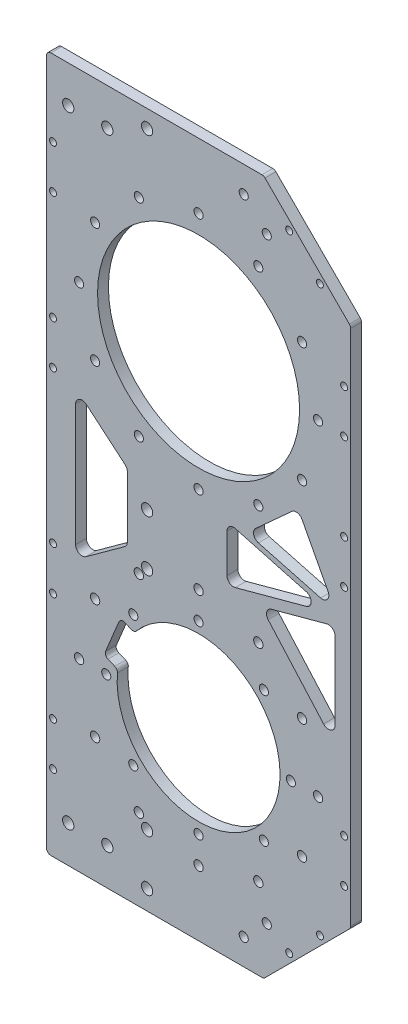
SolidWorks part; units mm, degrees
material "Thornel Mat VMA"
ref_plane "前视基准面" through (0, 0, 0) normal (0, 0, 1) x (1, 0, 0)
ref_plane "上视基准面" through (0, 0, 0) normal (0, 1, 0) x (1, 0, 0)
ref_plane "右视基准面" through (0, 0, 0) normal (1, 0, 0) x (0, 0, -1)
other "Configuration Table"
sketch "草图1" plane through (0, 0, 0) normal (0, 0, 1) x (1, 0, 0)
  line L1 (-70, -160) -> (70, -160)
  line L2 (-70, -160) -> (-70, 160)
  line L3 (-70, 160) -> (70, 160)
  line L4 (70, -160) -> (70, 160)
  line L5 (-70, -160) -> (70, 160) construction
  line L6 (-70, 160) -> (70, -160) construction
  point P0 (0, 0)
  dimension "D1" = 140
  dimension "D2" = 320
extrude "凸台-拉伸1" add sketch "草图1" along normal blind 5
sketch "草图2" plane through (0, 0, 5) normal (0, 0, 1) x (1, 0, 0)
  line L0 (-70, 0) -> (70, 0) construction
  line L1 (-70, 160) -> (-70, -160) construction
  line L2 (70, -160) -> (70, 160) construction
  line L3 (0, -75) -> (0, 75) construction
  circle A0 centre (0, 75) radius 46.5
  circle A1 centre (0, -75) radius 37.5
  circle A2 centre (0, -75) radius 42.5 construction
  circle A3 centre (42.5, -75) radius 2.1
  circle A4 centre (30.052, -105.052) radius 2.1
  circle A5 centre (0, -117.5) radius 2.1
  circle A6 centre (-30.052, -105.052) radius 2.1
  circle A7 centre (-42.5, -75) radius 2.1
  circle A8 centre (-30.052, -44.948) radius 2.1
  circle A9 centre (0, -32.5) radius 2.1
  circle A10 centre (30.052, -44.948) radius 2.1
  point P29 (0, -75)
  dimension "D1" = 75
  dimension "D2" = 93
  dimension "D3" = 150
  dimension "D4" = 70
  dimension "D5" = 85
  dimension "D6" = 4.2
  dimension "D8" = 75
  dimension "D7" = 8
extrude "切除-拉伸1" cut sketch "草图2" against normal blind 5
sketch "草图3" plane through (0, 0, 5) normal (0, 0, 1) x (1, 0, 0)
  line L0 (0, -75) -> (-30.052, -44.948) construction
  line L1 (0, -75) -> (-42.5, -75) construction
  line L2 (0, -75) -> (-43.6723, -56.9103) construction
  line L3 (-43.5537, -67.7834) -> (-17.685, -78.4985)
  line L4 (-43.5537, -67.7834) -> (-35.9, -49.3058)
  line L5 (-17.685, -78.4985) -> (-10.0314, -60.021)
  line L6 (-35.9, -49.3058) -> (-10.0314, -60.021)
  line L7 (-43.5537, -67.7834) -> (-10.0314, -60.021) construction
  line L8 (-17.685, -78.4985) -> (-35.9, -49.3058) construction
  point P8 (-26.7925, -63.9022)
  dimension "D1" = 22.5
  dimension "D2" = 20
  dimension "D3" = 15
  dimension "D4" = 28
extrude "切除-拉伸2" cut sketch "草图3" against normal blind 5
sketch "草图4" plane through (0, 0, 5) normal (0, 0, 1) x (1, 0, 0)
  circle A0 centre (0, -75) radius 55 construction
  circle A1 centre (0, -20) radius 2.15
  circle A2 centre (27.5, -27.3686) radius 2.15
  circle A3 centre (47.6314, -47.5) radius 2.15
  circle A4 centre (55, -75) radius 2.15
  circle A5 centre (47.6314, -102.5) radius 2.15
  circle A6 centre (27.5, -122.6314) radius 2.15
  circle A7 centre (0, -130) radius 2.15
  circle A8 centre (-27.5, -122.6314) radius 2.15
  circle A9 centre (-47.6314, -102.5) radius 2.15
  circle A10 centre (-55, -75) radius 2.15
  circle A11 centre (-47.6314, -47.5) radius 2.15
  circle A12 centre (-27.5, -27.3686) radius 2.15
  point P30 (0, -75)
  dimension "D1" = 110
  dimension "D2" = 4.3
  dimension "D3" = 12
extrude "切除-拉伸3" cut sketch "草图4" against normal blind 5
sketch "草图5" plane through (0, 0, 0) normal (0, 0, -1) x (-1, 0, 0)
  circle A0 centre (0, 75) radius 55 construction
  circle A1 centre (0, 130) radius 2.1
  circle A2 centre (27.5, 122.6314) radius 2.1
  circle A3 centre (47.6314, 102.5) radius 2.1
  circle A4 centre (55, 75) radius 2.1
  circle A5 centre (47.6314, 47.5) radius 2.1
  circle A6 centre (27.5, 27.3686) radius 2.1
  circle A7 centre (0, 20) radius 2.1
  circle A8 centre (-27.5, 27.3686) radius 2.1
  circle A9 centre (-47.6314, 47.5) radius 2.1
  circle A10 centre (-55, 75) radius 2.1
  circle A11 centre (-47.6314, 102.5) radius 2.1
  circle A12 centre (-27.5, 122.6314) radius 2.1
  point P29 (0, 75)
  dimension "D1" = 110
  dimension "D2" = 4.2
  dimension "D3" = 12
extrude "切除-拉伸4" cut sketch "草图5" against normal blind 15
sketch "草图6" plane through (0, 0, 5) normal (0, 0, 1) x (1, 0, 0)
  line L0 (30, 160) -> (70, 120)
  line L1 (70, 160) -> (-70, 160) construction
  line L2 (70, -160) -> (70, 160) construction
  line L3 (70, 120) -> (70, 160)
  line L4 (70, 160) -> (30, 160)
  line L5 (70, -120) -> (70, -160)
  line L6 (70, -160) -> (30, -160)
  line L7 (-70, -160) -> (70, -160) construction
  line L8 (30, -160) -> (70, -120)
  dimension "D1" = 45
  dimension "D2" = 45
  dimension "D3" = 40
  dimension "D4" = 40
extrude "切除-拉伸5" cut sketch "草图6" against normal blind 10
sketch "草图7" plane through (0, 0, 5) normal (0, 0, 1) x (1, 0, 0)
  line L0 (70, -115.7574) -> (25.7574, -160) construction
  line L1 (70, -120) -> (70, 120) construction
  line L2 (-70, -160) -> (30, -160) construction
  line L3 (70, -120) -> (30, -160) construction
  line L4 (-70, 0) -> (70, 0) construction
  line L5 (-70, 160) -> (-70, -160) construction
  line L6 (70, 115.7574) -> (25.7574, 160) construction
  circle A0 centre (41.7157, -144.0416) radius 1.6
  circle A1 centre (55.8579, -129.8995) radius 1.6
  circle A2 centre (55.8579, 129.8995) radius 1.6
  circle A3 centre (41.7157, 144.0416) radius 1.6
  dimension "D2" = 3.2
  dimension "D3" = 20
  dimension "D4" = 20
  dimension "D1" = 3
extrude "切除-拉伸6" cut sketch "草图7" against normal blind 327
fillet "圆角1" radius 2 9 edges at (70, -120, 2.5) (30, -160, 2.5) (-70, 160, 2.5) (30, 160, 2.5) (70, 120, 2.5) (-37.2178, -70.4078, 2.5) (-29.5641, -51.9302, 2.5) (-35.9, -49.3058, 2.5) (-70, -160, 2.5)
fillet "圆角2" radius 2 1 edges at (-43.5537, -67.7834, 2.5)
sketch "草图9" plane through (0, 0, 5) normal (0, 0, 1) x (1, 0, 0)
  line L0 (-23.7, 160) -> (-23.7, -160) construction
  line L1 (29.1716, 160) -> (-68, 160) construction
  line L2 (-68, -160) -> (29.1716, -160) construction
  line L3 (-70, 0.25) -> (70, 0.25) construction
  line L4 (-70, 158) -> (-70, -158) construction
  line L5 (70, -119.1716) -> (70, 119.1716) construction
  circle A0 centre (-23.7, 0) radius 2.6
  circle A1 centre (-23.7, -23.5) radius 2.6
  circle A2 centre (-23.7, -151) radius 2.6
  circle A3 centre (-23.7, -127.5) radius 2.6
  dimension "D2" = 5.2
  dimension "D3" = 23.5
  dimension "D5" = 23.5
  dimension "D6" = 9
  dimension "D1" = 159.75
  dimension "D4" = 46.3
extrude "切除-拉伸8" cut sketch "草图9" against normal blind 10
sketch "草图10" plane through (0, 0, 5) normal (0, 0, 1) x (1, 0, 0)
  line L0 (-68, -160) -> (29.1716, -160) construction
  line L1 (-70, 158) -> (-70, -158) construction
  line L2 (-70, 0) -> (70, 0) construction
  line L3 (70, -119.1716) -> (70, 119.1716) construction
  line L4 (-60, 143) -> (-42, 143) construction
  circle A0 centre (-60, -143) radius 2.6
  circle A1 centre (-60, 143) radius 2.6
  circle A2 centre (-42, 143) radius 2.6
  circle A3 centre (-42, -143) radius 2.6
  dimension "D1" = 17
  dimension "D2" = 5.2
  dimension "D3" = 10
  dimension "D4" = 5.2
  dimension "D5" = 18
extrude "切除-拉伸9" cut sketch "草图10" against normal blind 10
sketch "草图11" plane through (0, 0, 5) normal (0, 0, 1) x (1, 0, 0)
  line L0 (29.1716, 160) -> (-68, 160) construction
  line L1 (-70, 158) -> (-70, -158) construction
  circle A0 centre (-23.7, 152) radius 2.6
  dimension "D1" = 5.2
  dimension "D2" = 8
  dimension "D3" = 46.3
extrude "切除-拉伸10" cut sketch "草图11" against normal blind 10
sketch "草图12" plane through (0, 0, 5) normal (0, 0, 1) x (1, 0, 0)
  line L0 (67, 123) -> (67, -123) construction
  line L1 (30.5858, 159.4142) -> (69.4142, 120.5858) construction
  line L2 (69.4142, -120.5858) -> (30.5858, -159.4142) construction
  line L3 (70, -119.1716) -> (70, 119.1716) construction
  circle A0 centre (67, -104.5858) radius 1.6
  circle A1 centre (67, -84.5858) radius 1.6
  circle A2 centre (67, 94.5858) radius 1.6
  circle A3 centre (67, 74.5858) radius 1.6
  circle A4 centre (67, 34.5858) radius 1.6
  circle A5 centre (67, 14.5858) radius 1.6
  dimension "D2" = 3.2
  dimension "D3" = 20
  dimension "D4" = 20
  dimension "D5" = 20
  dimension "D6" = 26
  dimension "D7" = 40
  dimension "D8" = 16
  dimension "D1" = 3
extrude "切除-拉伸11" cut sketch "草图12" against normal blind 10
sketch "草图13" plane through (0, 0, 5) normal (0, 0, 1) x (1, 0, 0)
  line L0 (8.7868, 160) -> (70, 98.7868) construction
  line L1 (29.1716, 160) -> (-68, 160) construction
  line L2 (70, -119.1716) -> (70, 119.1716) construction
  line L3 (30.5858, 159.4142) -> (69.4142, 120.5858) construction
  line L4 (-70, 0) -> (70, 0) construction
  line L5 (-70, 158) -> (-70, -158) construction
  line L6 (8.7868, -160) -> (70, -98.7868) construction
  circle A0 centre (20.7868, 148) radius 2.1
  circle A1 centre (31.3934, 137.3934) radius 2.1
  circle A2 centre (31.3934, -137.3934) radius 2.1
  circle A3 centre (20.7868, -148) radius 2.1
  dimension "D2" = 4.2
  dimension "D3" = 15
  dimension "D4" = 12
  dimension "D1" = 15
extrude "切除-拉伸12" cut sketch "草图13" against normal blind 10
sketch "草图14" plane through (0, 0, 5) normal (0, 0, 1) x (1, 0, 0)
  line L0 (13.0829, 13.8401) -> (13.0829, -11.7624)
  line L1 (13.0829, -11.7624) -> (60.3054, 1.0388)
  line L2 (60.3054, 1.0388) -> (13.0829, 13.8401)
  line L3 (62.8087, -3.1145) -> (28.8071, -12.3318)
  line L4 (28.8071, -12.3318) -> (62.8087, -50.6783)
  line L5 (62.8087, -50.6783) -> (62.8087, -3.1145)
  line L6 (45.8053, 35.2514) -> (22.2063, 13.8401)
  line L7 (22.2063, 13.8401) -> (62.8087, 3.012)
  line L8 (62.8087, 3.012) -> (45.8053, 35.2514)
  line L9 (-56.6195, 32.2096) -> (-56.6195, -36.2538)
  line L10 (-56.6195, -36.2538) -> (-32.7974, -18.9626)
  line L11 (-32.7974, -18.9626) -> (-32.7974, 12.0751)
  line L12 (-32.7974, 12.0751) -> (-56.6195, 32.2096)
extrude "切除-拉伸13" cut sketch "草图14" against normal blind 10
fillet "圆角3" radius 3 6 edges at (60.3054, 1.0388, 2.5) (13.0829, 13.8401, 2.5) (62.8087, -50.6783, 2.5) (28.8071, -12.3318, 2.5) (62.8087, -3.1145, 2.5) (13.0829, -11.7624, 2.5)
fillet "圆角5" radius 3 3 edges at (62.8087, 3.012, 2.5) (45.8053, 35.2514, 2.5) (22.2063, 13.8401, 2.5)
fillet "圆角6" radius 3 4 edges at (-56.6195, -36.2538, 2.5) (-32.7974, 12.0751, 2.5) (-32.7974, -18.9626, 2.5) (-56.6195, 32.2096, 2.5)
sketch "草图15" plane through (0, 0, 5) normal (0, 0, 1) x (1, 0, 0)
  line L0 (-67, 160) -> (-67, -160) construction
  line L1 (29.1716, 160) -> (-68, 160) construction
  line L2 (-68, -160) -> (29.1716, -160) construction
  line L3 (-70, 158) -> (-70, -158) construction
  line L4 (-70, 0) -> (70, 0) construction
  line L5 (70, -119.1716) -> (70, 119.1716) construction
  circle A0 centre (-67, -125) radius 1.6
  circle A1 centre (-67, -105) radius 1.6
  circle A2 centre (-67, -35) radius 1.6
  circle A3 centre (-67, -55) radius 1.6
  circle A4 centre (-67, 55) radius 1.6
  circle A5 centre (-67, 35) radius 1.6
  circle A6 centre (-67, 105) radius 1.6
  circle A7 centre (-67, 125) radius 1.6
  dimension "D2" = 3.2
  dimension "D3" = 20
  dimension "D4" = 50
  dimension "D5" = 20
  dimension "D6" = 35
  dimension "D1" = 3
extrude "切除-拉伸14" cut sketch "草图15" against normal blind 10
equation "\"、\"=10"
